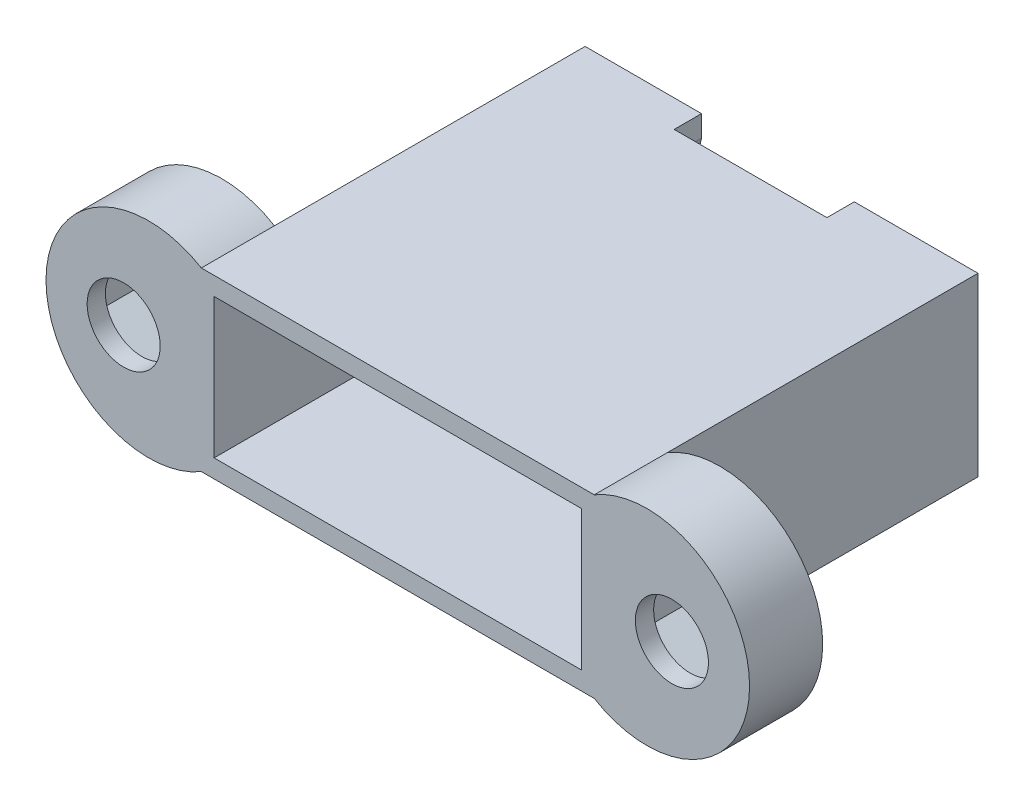
SolidWorks part; units mm, degrees
ref_plane "Front Plane" through (0, 0, 0) normal (0, 0, 1) x (1, 0, 0)
ref_plane "Top Plane" through (0, 0, 0) normal (0, 1, 0) x (1, 0, 0)
ref_plane "Right Plane" through (0, 0, 0) normal (1, 0, 0) x (0, 0, -1)
sketch "Sketch1" plane through (0, 0, 0) normal (0, 0, 1) x (1, 0, 0)
  line L5 (-10.0784, 4.9265) -> (11.4216, 4.9265)
  line L6 (-10.0784, 4.9265) -> (-10.0784, -4.7235)
  line L7 (-10.0784, -4.7235) -> (11.4216, -4.7235)
  line L8 (11.4216, 4.9265) -> (11.4216, -4.7235)
  point P4 (0.4216, 0.1015)
  dimension "D1" = 9.65
  dimension "D2" = 21.5
extrude "Boss-Extrude1" add sketch "Sketch1" along normal blind 21
sketch "Sketch3" plane through (0, 0, 21) normal (0, 0, 1) x (1, 0, 0)
  line L0 (11.4216, -4.7235) -> (11.4216, 4.9265) construction
  line L5 (-9.3784, 3.9265) -> (10.7216, 3.9265)
  line L6 (-9.3784, 3.9265) -> (-9.3784, -3.7235)
  line L7 (-9.3784, -3.7235) -> (10.7216, -3.7235)
  line L8 (10.7216, 3.9265) -> (10.7216, -3.7235)
  line L9 (-9.3784, 3.9265) -> (10.7216, -3.7235) construction
  line L10 (-9.3784, -3.7235) -> (10.7216, 3.9265) construction
  line L11 (-10.0784, -4.7235) -> (11.4216, -4.7235) construction
  line L13 (-10.0784, 4.9265) -> (-10.0784, -4.7235) construction
  point P4 (0.6716, 0.1015)
  dimension "D1" = 20.1
  dimension "D2" = 7.65
  dimension "D3" = 0.7
  dimension "D4" = 1
  dimension "D5" = 0.7
extrude "Cut-Extrude1" cut sketch "Sketch3" against normal blind 19.6
sketch "Sketch5" plane through (0, 0, 1.4) normal (0, 0, 1) x (1, 0, 0)
  line L1 (-0.8284, 2.9265) -> (1.6716, 2.9265) construction
  line L4 (-0.8284, 5.9265) -> (1.6716, 5.9265)
  line L5 (-0.8284, -0.0735) -> (1.6716, -0.0735)
  arc A0 (-0.8284, 5.9265) -> (-0.8284, -0.0735) centre (-0.8284, 2.9265) ccw
  arc A1 (1.6716, -0.0735) -> (1.6716, 5.9265) centre (1.6716, 2.9265) ccw
  point P3 (0.4216, 0.1297)
  point P9 (0.4216, 2.9265)
  dimension "D2" = 6
extrude "Cut-Extrude2" cut sketch "Sketch5" against normal blind 19.6
sketch "Sketch20" plane through (0, 0, 21) normal (0, 0, 1) x (1, 0, 0)
  line L0 (-18.5784, 0.1015) -> (-10.0784, 0.1015) construction
  line L20 (-10.0784, 4.9265) -> (-10.0784, -4.7235) construction
  line L21 (-10.0784, 4.9265) -> (-10.0784, -4.7235)
  arc A0 (-10.0784, 4.9265) -> (-10.0784, -4.7235) centre (-12.9589, 0.1015) ccw
  dimension "D1" = 8.5
extrude "Boss-Extrude2" add sketch "Sketch20" against normal blind 4
sketch "Sketch21" plane through (0, 0, 17) normal (0, 0, -1) x (-1, 0, 0)
  line L0 (18.5784, 0.1015) -> (10.0784, 0.1015) construction
  line L1 (10.0784, 4.9265) -> (10.0784, -4.7235) construction
  line L9 (14.3284, 3.8515) -> (11.0808, 1.9765)
  line L16 (11.0808, 1.9765) -> (11.0808, -1.7735)
  line L17 (11.0808, -1.7735) -> (14.3284, -3.6485)
  line L18 (14.3284, -3.6485) -> (17.576, -1.7735)
  line L19 (17.576, -1.7735) -> (17.576, 1.9765)
  line L20 (17.576, 1.9765) -> (14.3284, 3.8515)
  arc A0 (10.0784, -4.7235) -> (10.0784, 4.9265) centre (12.9589, 0.1015) ccw construction
  circle A1 centre (14.3284, 0.1015) radius 3.2476 construction
  point P8 (11.0808, 0.1015)
  dimension "D1" = 7.5
  dimension "D2" = 1.0024
extrude "Cut-Extrude3" cut sketch "Sketch21" against normal blind 3
sketch "Sketch22" plane through (0, 0, 20) normal (0, 0, -1) x (-1, 0, 0)
  line L0 (14.3284, 3.8515) -> (14.3284, -3.6485) construction
  circle A1 centre (14.3284, 0.1015) radius 2
  dimension "D1" = 4
extrude "Cut-Extrude4" cut sketch "Sketch22" against normal blind 3
sketch "Sketch23" plane through (0, 0, 21) normal (0, 0, 1) x (1, 0, 0)
  line L0 (11.4216, 4.9265) -> (11.4216, -4.7235)
  line L1 (11.4216, 0.1015) -> (19.9216, 0.1015) construction
  arc A0 (11.4216, 4.9265) -> (11.4216, -4.7235) centre (14.3022, 0.1015) cw
  dimension "D1" = 8.5
extrude "Boss-Extrude3" add sketch "Sketch23" against normal blind 4
sketch "Sketch24" plane through (0, 0, 17) normal (0, 0, -1) x (-1, 0, 0)
  line L0 (-19.9216, 0.1015) -> (-11.4216, 0.1015) construction
  line L1 (-11.4216, -4.7235) -> (-11.4216, 4.9265) construction
  line L3 (-15.6716, 3.8515) -> (-18.9192, 1.9765)
  line L4 (-18.9192, 1.9765) -> (-18.9192, -1.7735)
  line L5 (-18.9192, -1.7735) -> (-15.6716, -3.6485)
  line L6 (-15.6716, -3.6485) -> (-12.424, -1.7735)
  line L7 (-12.424, -1.7735) -> (-12.424, 1.9765)
  line L8 (-12.424, 1.9765) -> (-15.6716, 3.8515)
  arc A0 (-11.4216, 4.9265) -> (-11.4216, -4.7235) centre (-14.3022, 0.1015) ccw construction
  circle A1 centre (-15.6716, 0.1015) radius 3.2476 construction
  point P8 (-12.424, 0.1015)
  dimension "D1" = 7.5
  dimension "D2" = 1.0024
extrude "Cut-Extrude5" cut sketch "Sketch24" against normal blind 3
sketch "Sketch25" plane through (0, 0, 20) normal (0, 0, -1) x (-1, 0, 0)
  line L0 (-15.6716, -3.6485) -> (-15.6716, 3.8515) construction
  line L1 (-12.424, 1.9765) -> (-15.6716, 3.8515) construction
  line L2 (-15.6716, 3.8515) -> (-18.9192, 1.9765) construction
  circle A0 centre (-15.6716, 0.1015) radius 2
  dimension "D1" = 4
extrude "Cut-Extrude6" cut sketch "Sketch25" against normal blind 3
sketch "Sketch26" plane through (0, 4.9265, 0) normal (0, 1, 0) x (1, 0, 0)
  line L1 (-3.7078, 0) -> (4.6524, 0)
  line L2 (-3.7078, 0) -> (-3.7078, -1.4981)
  line L3 (-3.7078, -1.4981) -> (4.6524, -1.4981)
  line L4 (4.6524, 0) -> (4.6524, -1.4981)
  line L5 (0.4723, -1.4981) -> (0.4723, 0) construction
  line L6 (-3.7078, -0.749) -> (4.6524, -0.749) construction
  point P312 (0.4723, -0.749)
  dimension "D1" = 8.3602
extrude "Cut-Extrude7" cut sketch "Sketch26" against normal blind 2
